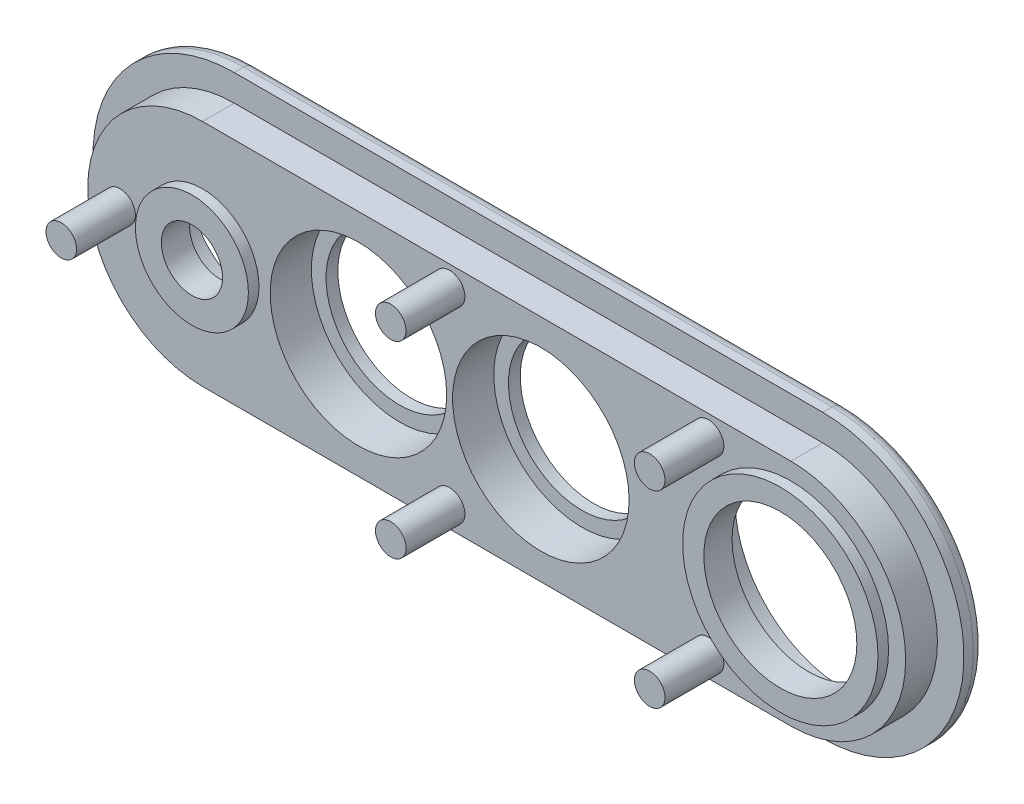
SolidWorks part; units mm, degrees
ref_plane "Спереди" through (0, 0, 0) normal (0, 0, 1) x (1, 0, 0)
ref_plane "Сверху" through (0, 0, 0) normal (0, 1, 0) x (1, 0, 0)
ref_plane "Справа" through (0, 0, 0) normal (1, 0, 0) x (0, 0, -1)
other "Configuration Table"
sketch "Эскиз1" plane through (0, 0, 0) normal (0, 0, 1) x (1, 0, 0)
  line L1 (0, 0) -> (50, 0)
  line L3 (0, -24) -> (50, -24)
  arc A0 (0, 0) -> (0, -24) centre (0, -12) ccw
  arc A1 (50, -24) -> (50, 0) centre (50, -12) ccw
  dimension "D1" = 24
  dimension "D2" = 50
extrude "Бобышка-Вытянуть1" add sketch "Эскиз1" along normal blind 4.5
sketch "Эскиз2" plane through (0, 0, 4.5) normal (0, 0, 1) x (1, 0, 0)
  line L0 (0, -12) -> (50, -12) construction
  line L1 (0, -2.25) -> (50, -2.25)
  line L2 (0, -21.75) -> (50, -21.75)
  line L3 (0, -12) -> (50, -12) construction
  line L4 (0, 0.0123) -> (50, 0.0123)
  line L5 (0, -24.0123) -> (50, -24.0123)
  arc A0 (0, -2.25) -> (0, -21.75) centre (0, -12) ccw
  arc A1 (50, -21.75) -> (50, -2.25) centre (50, -12) ccw
  arc A2 (0, 0.0123) -> (0, -24.0123) centre (0, -12) ccw
  arc A3 (50, -24.0123) -> (50, 0.0123) centre (50, -12) ccw
  point P4 (25, -12)
  point P11 (25, -12)
  dimension "D1" = 19.5
extrude "Вырез-Вытянуть1" cut sketch "Эскиз2" against normal blind 2.7
sketch "Эскиз3" plane through (0, 0, 4.5) normal (0, 0, 1) x (1, 0, 0)
  circle A0 centre (0, -12) radius 2.6
  circle A1 centre (50, -12) radius 6.5
  circle A2 centre (13.25, -12) radius 6.25
  circle A3 centre (28.75, -12) radius 6.25
  dimension "D1" = 5.2
  dimension "D2" = 13
  dimension "D3" = 12.5
  dimension "D5" = 12.5
  dimension "D4" = 13.25
  dimension "D6" = 15.5
  dimension "D7" = 50
extrude "Вырез-Вытянуть2" cut sketch "Эскиз3" against normal through all
sketch "Эскиз4" plane through (0, 0, 0) normal (0, 0, -1) x (-1, 0, 0)
  circle A0 centre (0, -12) radius 5.5
  circle A1 centre (-50, -12) radius 9.25
  dimension "D1" = 18.5
  dimension "D2" = 11
extrude "Вырез-Вытянуть3" cut sketch "Эскиз4" against normal blind 3
sketch "Эскиз5" plane through (0, 0, 0) normal (0, 0, -1) x (-1, 0, 0)
  circle A0 centre (-40, -4) radius 1.55
  circle A1 centre (-7, -4) radius 1.55
  circle A2 centre (-7, -20) radius 1.55
  circle A3 centre (-40, -20) radius 1.55
  circle A4 centre (-50, -12) radius 9.25 construction
  circle A5 centre (0, -12) radius 5.5 construction
  dimension "D1" = 3.1
  dimension "D2" = 8
  dimension "D3" = 8
  dimension "D4" = 10
  dimension "D5" = 7
extrude "Вырез-Вытянуть4" [suppressed] cut sketch "Эскиз5" against normal through all
sketch "Эскиз6" [suppressed] plane through (0, 0, 0) normal (0, 0, -1) x (-1, 0, 0)
  circle A0 centre (-40, -4) radius 3.2
  circle A1 centre (-7, -4) radius 3.2
  circle A2 centre (-7, -20) radius 3.2
  circle A3 centre (-40, -20) radius 3.2
  dimension "D1" = 6.4
extrude "Вырез-Вытянуть5" [suppressed] cut sketch "Эскиз6" against normal blind 2.5
fillet "Скругление1" radius 1 4 edges at (62, -12, 0) (25, -24, 0) (-12, -12, 0) (25, 0, 0)
sketch "Эскиз7" plane through (0, 0, 4.5) normal (0, 0, 1) x (1, 0, 0)
  circle A0 centre (28.75, -12) radius 7.5
  circle A1 centre (13.25, -12) radius 7.5
  dimension "D1" = 15
  dimension "D2" = 15
extrude "Вырез-Вытянуть6" cut sketch "Эскиз7" against normal blind 3.5
fillet "Скругление2" [suppressed] radius 1
sketch "Эскиз8" plane through (0, 0, 4.5) normal (0, 0, 1) x (1, 0, 0)
  line L0 (0, -12) -> (50, -12) construction
  line L1 (0, -2.5905) -> (50, -2.5905)
  line L2 (0, -21.4095) -> (50, -21.4095)
  line L3 (0, -4.3905) -> (50, -4.3905)
  line L4 (0, -19.6095) -> (50, -19.6095)
  line L6 (-10.8433, -10.8768) -> (-9.3422, -10.8768)
  line L7 (-10.8433, -10.8768) -> (-10.8433, -13.4479)
  line L8 (-10.8433, -13.4479) -> (-9.2974, -13.4479)
  arc A0 (0, -2.5905) -> (-9.3422, -10.8768) centre (0, -12) ccw
  arc A1 (50, -21.4095) -> (50, -2.5905) centre (50, -12) ccw
  arc A2 (50, -19.6095) -> (50, -4.3905) centre (50, -12) ccw
  arc A3 (0, -4.3905) -> (0, -19.6095) centre (0, -12) ccw
  arc A4 (-9.2974, -13.4479) -> (0, -21.4095) centre (0, -12) ccw
  arc A5 (0, -2.5905) -> (0, -21.4095) centre (0, -12) ccw construction
  point P4 (25, -12)
  dimension "D1" = 1.8
extrude "Вырез-Вытянуть7" [suppressed] cut sketch "Эскиз8" against normal blind 1
sketch "Эскиз9" plane through (0, 0, 4.5) normal (0, 0, 1) x (1, 0, 0)
  line L0 (0, -12) -> (-17.3902, -12) construction
  circle A0 centre (21, -4) radius 1.3
  circle A1 centre (21, -20) radius 1.3
  circle A2 centre (0, -12) radius 2.6 construction
  circle A3 centre (-7, -12) radius 1.3
  circle A4 centre (43, -4) radius 1.3
  circle A5 centre (43, -20) radius 1.3
  point P12 (-7, -12)
  dimension "D1" = 2.6
  dimension "D2" = 2.6
  dimension "D4" = 8
  dimension "D5" = 21
  dimension "D6" = 43
  dimension "D3" = 16
  dimension "D7" = 7
extrude "Бобышка-Вытянуть2" add sketch "Эскиз9" along normal blind 5
sketch "Эскиз10" plane through (0, 0, 4.5) normal (0, 0, 1) x (1, 0, 0)
  circle A0 centre (0, -12) radius 2.6
  circle A1 centre (0, -12) radius 4.8
  circle A2 centre (50, -12) radius 6.5
  circle A3 centre (50, -12) radius 8.3
  dimension "D1" = 16.6
  dimension "D2" = 9.6
extrude "Бобышка-Вытянуть3" add sketch "Эскиз10" along normal blind 0.9
